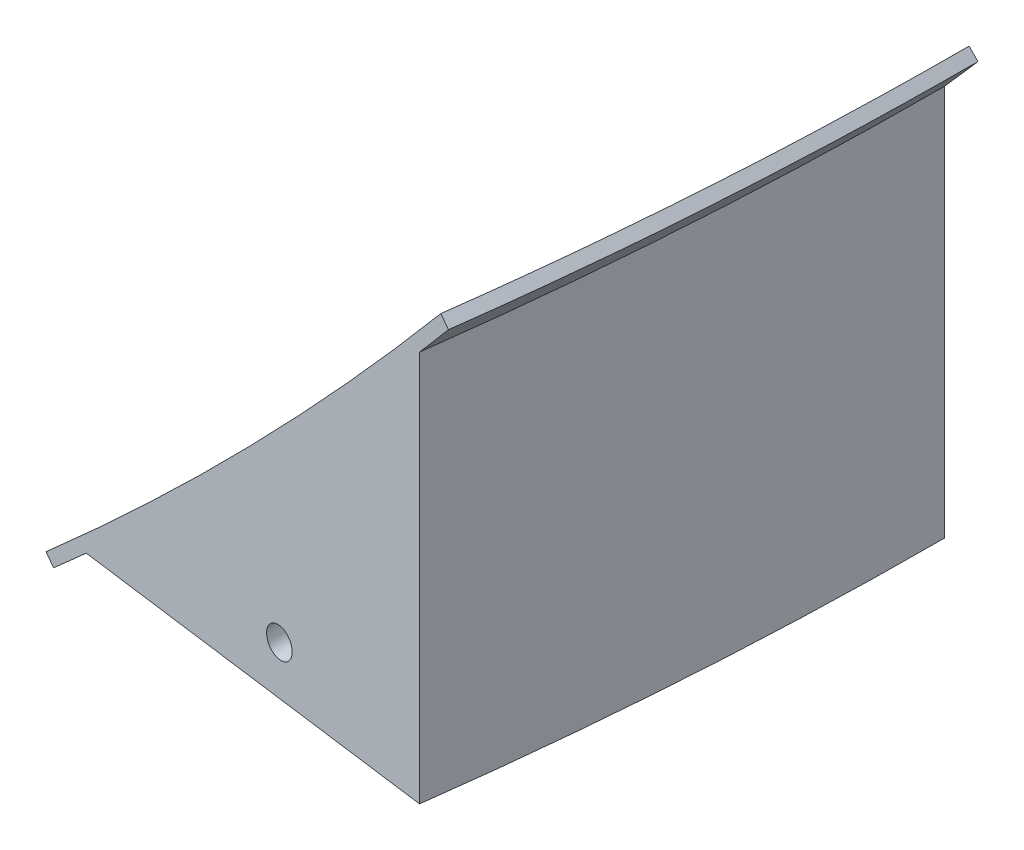
SolidWorks part; units mm, degrees
material "Nylon 101"
ref_plane "Front Plane" through (0, 0, 0) normal (0, 0, 1) x (1, 0, 0)
ref_plane "Top Plane" through (0, 0, 0) normal (0, 1, 0) x (1, 0, 0)
ref_plane "Right Plane" through (0, 0, 0) normal (1, 0, 0) x (0, 0, -1)
sketch "Sketch2" plane through (0, 0, 0) normal (0, 0, 1) x (1, 0, 0)
  line L0 (0, 993.0752) -> (0, 990.6)
  line L1 (0, -990.6) -> (0, -993.0752)
  line L4 (742.757, 659.1741) -> (742.757, 722.7151)
  line L5 (742.757, 722.7151) -> (681.0884, 722.7151)
  line L7 (742.9731, -658.9305) -> (742.9731, -735.9651)
  line L8 (742.9731, -735.9651) -> (666.7487, -735.9651)
  arc A0 (0, 990.6) -> (0, -990.6) centre (0, 0) cw
  arc A1 (0, -993.0752) -> (666.7487, -735.9651) centre (0, 0) ccw
  arc A2 (681.0884, 722.7151) -> (0, 993.0752) centre (0, 0) ccw
  arc A3 (742.9731, -658.9305) -> (742.757, 659.1741) centre (0, 0) ccw
  dimension "D1" = 990.6
revolve "Revolve2" add sketch "Sketch2" angle 7.5 about L0
sketch "Sketch4" plane through (0, -735.9651, 0) normal (0, -1, 0) x (1, 0, 0)
  line L1 (688.6335, 42.5614) -> (721.8835, 42.5614)
  line L2 (688.6335, 42.5614) -> (688.6335, 55.5614)
  line L3 (688.6335, 55.5614) -> (721.8835, 55.5614)
  line L4 (721.8835, 42.5614) -> (721.8835, 55.5614)
sketch "Sketch7" plane through (0, 722.7151, 0) normal (0, 1, 0) x (-1, 0, 0)
  line L1 (-731.6247, 39.9227) -> (-698.3747, 39.9227)
  line L2 (-731.6247, 39.9227) -> (-731.6247, 52.9227)
  line L3 (-731.6247, 52.9227) -> (-698.3747, 52.9227)
  line L4 (-698.3747, 39.9227) -> (-698.3747, 52.9227)
extrude "Cut-Extrude5" cut sketch "Sketch4" against normal blind 19
extrude "Cut-Extrude7" cut sketch "Sketch7" against normal blind 19
sketch "Sketch10" plane through (0, 0, 0) normal (0, 0, 1) x (1, 0, 0)
  line L0 (0, 0) -> (701.808, -701.808) construction
  line L2 (1625.1249, 1070.7942) -> (-510.1458, 1070.7942)
  line L3 (1625.1249, 1070.7942) -> (1625.1249, -535.7979)
  line L4 (1625.1249, -535.7979) -> (-510.1458, -535.7979)
  line L5 (-510.1458, 1070.7942) -> (-510.1458, -535.7979)
  line L6 (626.211, -838.358) -> (-340.2676, -838.358)
  line L7 (626.211, -838.358) -> (626.211, -1151.6956)
  line L8 (626.211, -1151.6956) -> (-340.2676, -1151.6956)
  line L9 (-340.2676, -838.358) -> (-340.2676, -1151.6956)
extrude "Cut-Extrude11" cut sketch "Sketch10" against normal through all and the other way through all
sketch "Sketch12" plane through (0, 0, 0) normal (0, 0, 1) x (1, 0, 0)
  line L0 (697.0492, -703.8542) -> (0, 0) construction
  arc A0 (527.6782, -838.358) -> (833.192, -535.7979) centre (0, 0) ccw construction
ref_plane "Plane3" through (698.791, -705.613, 0) normal (0.7037, -0.7105, 0) x (-0.7105, -0.7037, 0)
sketch "Sketch13" plane through (698.791, -705.613, 0) normal (0.7037, -0.7105, 0) x (-0.7105, -0.7037, 0)
  line L0 (-69.6818, -97.9088) -> (-74.2416, -183.6902)
  line L1 (-74.2416, -183.6902) -> (-254.5848, -153.9893)
  line L2 (-254.5848, -153.9893) -> (-254.5848, 36.2191)
  line L3 (-254.5848, 36.2191) -> (-86.4431, 59.0438)
  line L4 (-86.4431, 59.0438) -> (-74.2416, 0)
  line L5 (58.1343, -86.0968) -> (71.3823, -183.6902)
  line L6 (71.3823, -183.6902) -> (231.7813, -140.7995)
  line L7 (231.7813, -140.7995) -> (262.8142, 47.6315)
  line L8 (262.8142, 47.6315) -> (38.6488, 72.9438)
  line L9 (38.6488, 72.9438) -> (54.1248, 0)
  spline S0 degree 3 poles (2110.8426, -650.9962) (599.0037, 1458.8781) (-106.6483, 671.3029) (-39.6018, -768.3638) (730.932, -1420.6333) (2038.7488, 933.4431) knots -21.556865 -21.556865 -21.556865 -21.556865 0.5 0.5 22.524562 22.524562 22.524562 22.524562 only from (-74.2416, 0) to (-69.6818, -97.9088)
  spline S1 degree 3 poles (-74.2416, 0) (-74.2416, -16.3642) (-73.861, -32.7283) (-72.34, -65.3876) (-71.1997, -81.6827) (-69.6818, -97.9088) knots 0 0 0 0 0.5 0.5 1 1 1 1
  spline S2 degree 3 poles (2231.3106, -1026.8921) (723.6033, 1369.0013) (23.8412, 628.6745) (86.3531, -713.6227) (845.7209, -1315.8452) (2104.1948, 1321.8464) knots -22.89214 -22.89214 -22.89214 -22.89214 0.5 0.5 23.845611 23.845611 23.845611 23.845611 only from (54.1248, 0) to (58.1343, -86.0968)
  spline S3 degree 3 poles (54.1248, 0) (54.1248, -14.3912) (54.4595, -28.7824) (55.797, -57.5021) (56.7998, -71.8307) (58.1343, -86.0968) knots 0 0 0 0 0.5 0.5 1 1 1 1
  dimension "D1" = 10
  dimension "D2" = 10
extrude "Cut-Extrude12" cut sketch "Sketch13" against normal through all both and the other way through all
sketch "Sketch14" plane through (0, 0, 55.5614) normal (0, 0, -1) x (-1, 0, 0)
  circle A0 centre (-704.851, -726.4041) radius 2.9043
extrude "Cut-Extrude13" cut sketch "Sketch14" against normal through all both and the other way through all contours A0
